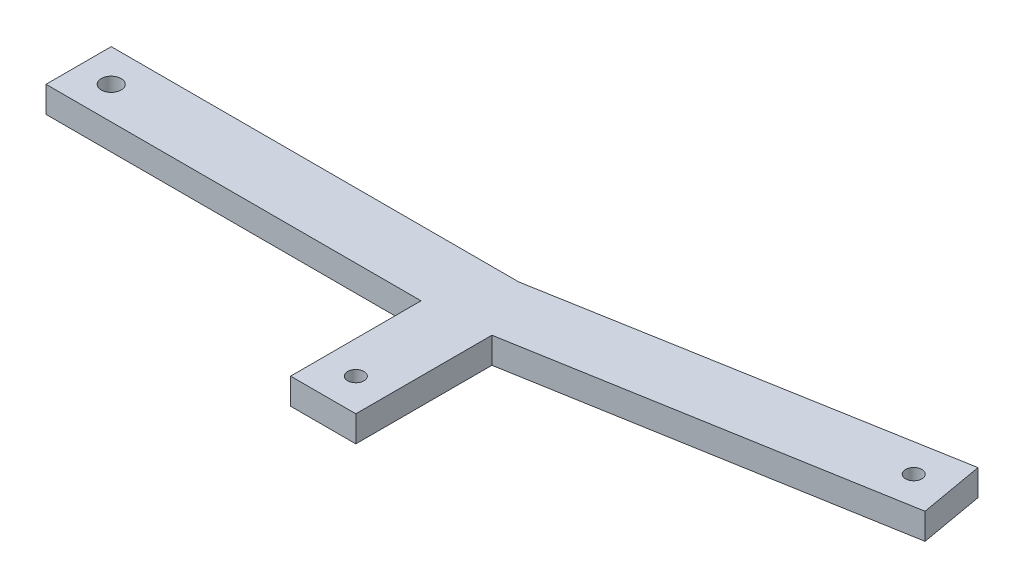
SolidWorks part; units mm, degrees
ref_plane "Front Plane" through (0, 0, 0) normal (0, 0, 1) x (1, 0, 0)
ref_plane "Top Plane" through (0, 0, 0) normal (0, 1, 0) x (1, 0, 0)
ref_plane "Right Plane" through (0, 0, 0) normal (1, 0, 0) x (0, 0, -1)
sketch "Sketch1" plane through (0, 0, 0) normal (0, 1, 0) x (1, 0, 0)
  line L0 (75.8618, 10) -> (195.5422, 31.1029)
  line L1 (65.8618, -10) -> (-49.1382, -10)
  line L2 (195.5422, 31.1029) -> (199.0183, 11.3888)
  line L3 (75.8618, 10) -> (-49.1382, 10)
  line L4 (-49.1382, -10) -> (-49.1382, 10)
  line L7 (85.8618, -8.2633) -> (199.0183, 11.3888)
  line L8 (65.8618, -50) -> (65.8618, -10)
  line L9 (85.8618, -50) -> (85.8618, -8.2633)
  line L10 (75.8618, -50) -> (65.8618, -50)
  line L11 (75.8618, -50) -> (85.8618, -50)
  circle A0 centre (-39.1382, 0) radius 3.05
  circle A1 centre (75.8618, -40) radius 2.5
  circle A2 centre (187.4322, 19.5093) radius 2.5
extrude "Boss-Extrude1" add sketch "Sketch1" along normal blind 8
